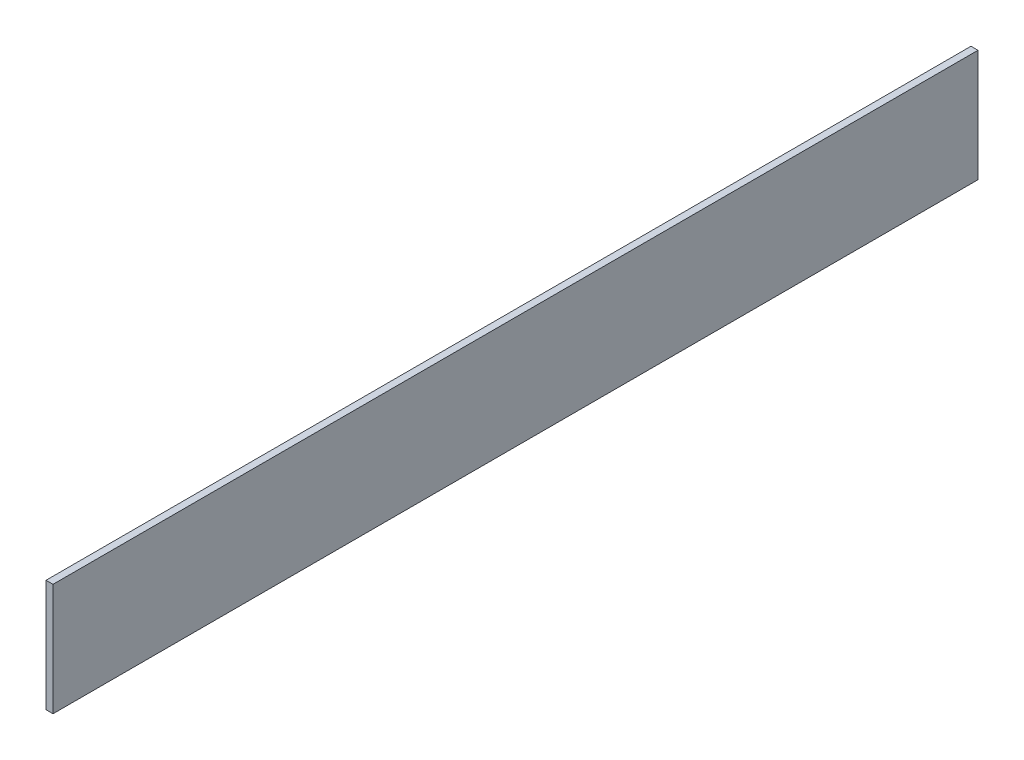
SolidWorks part; units mm, degrees
ref_plane "Front Plane" through (0, 0, 0) normal (0, 0, 1) x (1, 0, 0)
ref_plane "Top Plane" through (0, 0, 0) normal (0, 1, 0) x (1, 0, 0)
ref_plane "Right Plane" through (0, 0, 0) normal (1, 0, 0) x (0, 0, -1)
other "Configuration Table"
sketch "Sketch1" plane through (0, 0, 0) normal (0, 0, 1) x (1, 0, 0)
  line L1 (512.5, 552) -> (515, 552)
  line L2 (512.5, 552) -> (512.5, 592)
  line L3 (512.5, 592) -> (515, 592)
  line L4 (515, 552) -> (515, 592)
extrude "PACK_kalip_duvari_sag_1" add sketch "Sketch1" against normal blind 330 from offset 235 separate body
